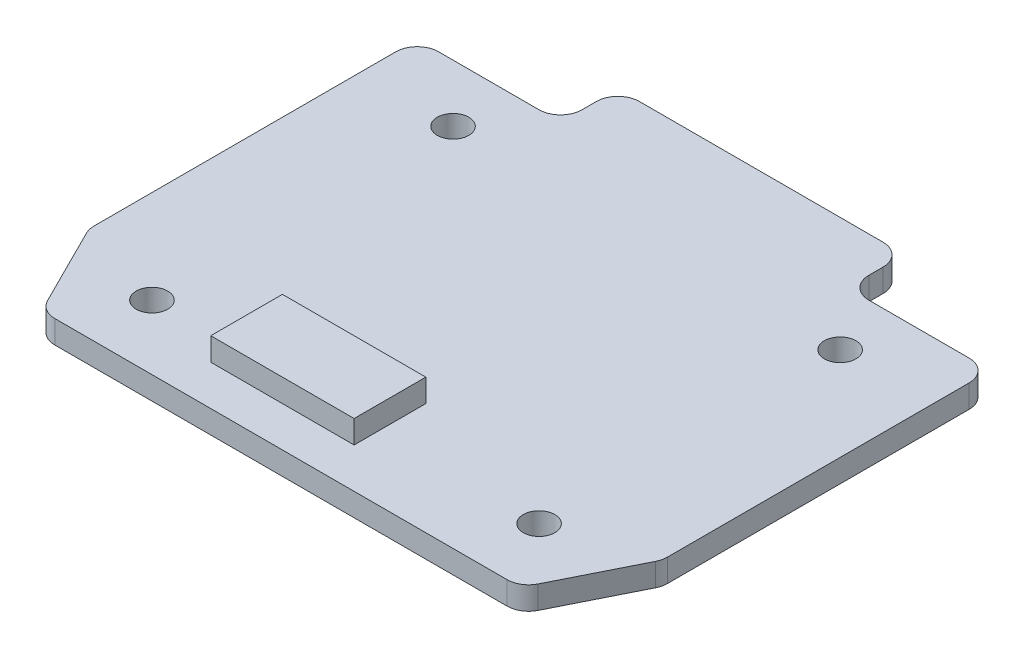
SolidWorks part; units mm, degrees
material "FR4_stuffedProtoboard"
ref_plane "Front Plane" through (0, 0, 0) normal (0, 0, 1) x (1, 0, 0)
ref_plane "Top Plane" through (0, 0, 0) normal (0, 1, 0) x (1, 0, 0)
ref_plane "Right Plane" through (0, 0, 0) normal (1, 0, 0) x (0, 0, -1)
sketch "Sketch1" plane through (0, 0, 0) normal (0, 1, 0) x (1, 0, 0)
  line L0 (-20, 14.75) -> (20, -14.75) construction
  line L1 (-20, 14.75) -> (-10, 14.75)
  line L2 (-20, 14.75) -> (-20, -14.75)
  line L3 (-20, -14.75) -> (20, -14.75)
  line L4 (20, 14.75) -> (20, -14.75)
  line L5 (10, 14.75) -> (20, 14.75)
  line L7 (-10, 14.75) -> (-10, 18.75)
  line L8 (-10, 18.75) -> (10, 18.75)
  line L9 (10, 14.75) -> (10, 18.75)
  line L10 (0, 15.75) -> (10, 18.75) construction
  line L11 (-10, 18.75) -> (0, 15.75) construction
  point P4 (0, 15.75)
  dimension "D1" = 40
  dimension "D2" = 29.5
  dimension "D3" = 20
  dimension "D4" = 4
  dimension "D5" = 20
extrude "Boss-Extrude1" add sketch "Sketch1" along normal blind 1.6
sketch "Sketch4" plane through (0, 0, 0) normal (0, -1, 0) x (1, 0, 0)
  line L0 (-2.2, -5.8223) -> (2.2, -5.8223) construction
  line L1 (-2.2, -0.8223) -> (-2.2, -5.8223) construction
  line L2 (2.2, -0.8223) -> (-2.2, -0.8223) construction
  line L3 (2.2, -5.8223) -> (2.2, -0.8223) construction
  line L12 (-2.2, -5.8223) -> (2.2, -5.8223)
  line L13 (-2.2, -0.8223) -> (-2.2, -5.8223)
  line L14 (2.2, -0.8223) -> (-2.2, -0.8223)
  line L15 (2.2, -5.8223) -> (2.2, -0.8223)
  circle A0 centre (0, -3.3223) radius 0.75 construction
  circle A1 centre (0, -3.3223) radius 0.75
  circle A2 centre (0, -3.3223) radius 3 construction
  circle A3 centre (0, -3.3223) radius 3
sketch "Sketch12" plane through (0, 1.6, 0) normal (0, 1, 0) x (1, 0, 0)
  line L0 (-16.7, -14.75) -> (-20, -8.15)
  line L1 (-20, -14.75) -> (20, -14.75) construction
  line L2 (-20, 14.75) -> (-20, -14.75) construction
  line L3 (-20, -8.15) -> (-20, -14.75)
  line L4 (-20, -14.75) -> (-16.7, -14.75)
  line L5 (16.7, -14.75) -> (20, -8.15)
  line L6 (20, -14.75) -> (20, 14.75) construction
  line L7 (20, -8.15) -> (20, -14.75)
  line L8 (20, -14.75) -> (16.7, -14.75)
  dimension "D1" = 6.6
  dimension "D2" = 3.3
extrude "Cut-Extrude4" cut sketch "Sketch12" against normal through all
hole_wizard "M2 Clearance Hole1" positions "Sketch2" profile "Sketch3" hole size "M2" standard "ANSI Metric"
sketch "Sketch2" plane through (0, 1.6, 0) normal (0, 1, 0) x (1, 0, 0)
  line L1 (-13.5, 10.75) -> (13.5, 10.75)
  line L2 (-13.5, 10.75) -> (-13.5, -10.25)
  line L3 (-13.5, -10.25) -> (13.5, -10.25)
  line L4 (13.5, 10.75) -> (13.5, -10.25)
  line L5 (-16.7, -14.75) -> (16.7, -14.75) construction
  point P0 (-13.5, 10.75)
  point P2 (13.5, 10.75)
  point P4 (13.5, -10.25)
  point P6 (-13.5, -10.25)
  point P142 (0, -10.25)
  dimension "D1" = 21
  dimension "D2" = 27
  dimension "D3" = 4.5
sketch "Sketch3" plane through (-13.5, 1.6, -10.75) normal (1, 0, 0) x (0, 0, 1)
  line L0 (0, 0) -> (0, 5.8609)
  line L1 (0, 5.8609) -> (1.1, 5.2)
  line L2 (1.1, 5.2) -> (1.1, 0)
  line L5 (1.1, 0) -> (0, 0)
  line L10 (0, 5.8609) -> (-1.1, 5.2) construction
  line L11 (0, -6.35) -> (0, 107.95) construction
  dimension "Hole Dia." = 2.2
  dimension "Hole Depth" = 5.2
  dimension "Drill Angle" = 118
hole_wizard "M2 Clearance Hole3" [suppressed] positions "Sketch8" profile "Sketch9" hole size "M2" standard "ANSI Metric"
sketch "Sketch8" plane through (0, 1.6, 0) normal (0, 1, 0) x (1, 0, 0)
  line L0 (-13.5, 12.75) -> (13.5, 12.75)
  line L1 (-13.5, 12.75) -> (-13.5, -10.25)
  line L2 (-13.5, -10.25) -> (13.5, -10.25)
  line L3 (13.5, 12.75) -> (13.5, -10.25)
  line L4 (-17, -14.75) -> (17, -14.75) construction
  point P3 (-13.5, 12.75)
  point P5 (13.5, 12.75)
  point P6 (13.5, -10.25)
  point P7 (-13.5, -10.25)
  point P14 (0, -10.25)
  dimension "D1" = 23
  dimension "D2" = 27
  dimension "D3" = 4.5
sketch "Sketch9" plane through (-13.5, 1.6, -12.75) normal (1, 0, 0) x (0, 0, 1)
  line L0 (0, 0) -> (0, 5.8309)
  line L1 (0, 5.8309) -> (1.05, 5.2)
  line L2 (1.05, 5.2) -> (1.05, 0)
  line L5 (1.05, 0) -> (0, 0)
  line L10 (0, 5.8309) -> (-1.05, 5.2) construction
  line L11 (0, -6.35) -> (0, 107.95) construction
  dimension "Hole Dia." = 2.1
  dimension "Hole Depth" = 5.2
  dimension "Drill Angle" = 118
sketch "Sketch10" [suppressed] plane through (0, 1.6, 0) normal (0, 1, 0) x (1, 0, 0)
  line L0 (-13.5, 12.75) -> (-13.5, 17.75) construction
  line L1 (-14.55, 12.75) -> (-14.55, 17.75)
  line L2 (-12.45, 12.75) -> (-12.45, 17.75)
  line L3 (17, 14.75) -> (-17, 14.75) construction
  line L4 (0, 14.75) -> (0, -14.75) construction
  line L5 (-17, -14.75) -> (17, -14.75) construction
  line L6 (13.5, 12.75) -> (13.5, 17.75) construction
  line L7 (14.55, 12.75) -> (14.55, 17.75)
  line L8 (12.45, 12.75) -> (12.45, 17.75)
  arc A0 (-14.55, 12.75) -> (-12.45, 12.75) centre (-13.5, 12.75) ccw
  arc A1 (-12.45, 17.75) -> (-14.55, 17.75) centre (-13.5, 17.75) ccw
  circle A2 centre (-13.5, 12.75) radius 1.05 construction
  arc A3 (14.55, 12.75) -> (12.45, 12.75) centre (13.5, 12.75) cw
  arc A4 (12.45, 17.75) -> (14.55, 17.75) centre (13.5, 17.75) cw
  point P3 (-13.5, 15.25)
  point P18 (13.5, 15.25)
  dimension "D1" = 3
extrude "Cut-Extrude2" [suppressed] cut sketch "Sketch10" against normal through all both and the other way through all
fillet "Fillet3" [suppressed] radius 1
sketch "Sketch11" plane through (0, 0, 0) normal (0, -1, 0) x (1, 0, 0)
  line L0 (-15, 14.1949) -> (15, 14.1949) construction
  line L4 (-15, 14.1949) -> (15, 14.1949)
  line L5 (15, 14.1949) -> (15, -14.75)
  line L6 (-15, -14.75) -> (15, -14.75)
  line L7 (-15, 14.1949) -> (-15, -14.75)
  line L8 (-10, 11.6949) -> (10, 11.6949) construction
  line L10 (10, -11.7488) -> (-10, -11.7488) construction
  line L12 (-10, 11.6949) -> (10, 11.6949)
  line L13 (-12, -9.748) -> (-12, 9.7506)
  line L14 (10, -11.7488) -> (-10, -11.7488)
  line L15 (12, 9.6375) -> (12, -9.748)
  line L16 (15, 9.25) -> (15, -11.75) construction
  line L17 (-15, 9.25) -> (-15, -11.75) construction
  line L18 (-10, -14.75) -> (-20, -14.75) construction
  circle A0 centre (13.5, -12.75) radius 1 construction
  circle A1 centre (13.5, -12.75) radius 1
  circle A2 centre (13.5, 10.25) radius 1 construction
  circle A3 centre (13.5, 10.25) radius 1
  circle A4 centre (-13.5, -12.75) radius 1 construction
  circle A5 centre (-13.5, -12.75) radius 1
  circle A6 centre (-13.5, 10.25) radius 1 construction
  circle A7 centre (-13.5, 10.25) radius 1
  arc A8 (10, 11.6949) -> (12, 9.6375) centre (10, 9.6941) cw
  arc A9 (-10, 11.6949) -> (-12, 9.7506) centre (-10, 9.6941) ccw
  ellipse E1 centre (-10, -9.748) end of major axis (-10, -7.7472) minor radius 2 (-12, -9.748) -> (-10, -11.7488) ccw construction
  ellipse E2 centre (10, -9.748) end of major axis (10, -7.7472) minor radius 2 (10, -11.7488) -> (12, -9.748) ccw construction
  ellipse E4 centre (10, 9.6941) end of major axis (10, 11.6949) minor radius 2 (11.2574, 11.25) -> (10, 11.6949) ccw construction
  ellipse E5 centre (-10, -9.748) end of major axis (-10, -7.7472) minor radius 2 (-12, -9.748) -> (-10, -11.7488) ccw
  ellipse E6 centre (10, -9.748) end of major axis (10, -7.7472) minor radius 2 (10, -11.7488) -> (12, -9.748) ccw
  ellipse E7 centre (-10, 9.6941) end of major axis (-10, 11.6949) minor radius 2 (-10, 11.6949) -> (-11.2574, 11.25) ccw construction
extrude "Cut-Extrude3" cut sketch "Sketch11" against normal blind 0.001
sketch "boardLayoutOrigin" [suppressed] plane through (0, 0, 0) normal (0, -1, 0) x (1, 0, 0)
  line L0 (20, 11.75) -> (20, -11.75) construction
  line L1 (-17, 14.75) -> (17, 14.75) construction
  point P0 (20, 14.75)
sketch "Sketch13" plane through (0, 1.6, 0) normal (0, 1, 0) x (1, 0, 0)
  line L0 (-20, 14.75) -> (-20, -8.15) construction
  line L1 (-7.7, -11.95) -> (2.3, -11.95)
  line L2 (-7.7, -11.95) -> (-7.7, -6.95)
  line L3 (-7.7, -6.95) -> (2.3, -6.95)
  line L4 (2.3, -11.95) -> (2.3, -6.95)
  line L5 (-7.7, -11.95) -> (2.3, -6.95) construction
  line L6 (-7.7, -6.95) -> (2.3, -11.95) construction
  line L7 (-16.7, -14.75) -> (16.7, -14.75) construction
  point P0 (-2.7, -9.45)
  dimension "D1" = 17.3
  dimension "D2" = 5.3
  dimension "D3" = 10
  dimension "D4" = 5
extrude "Boss-Extrude2" add sketch "Sketch13" along normal blind 1.6 separate body
fillet "Fillet1" radius 1.5 10 edges at (-20, 0.8, -14.75) (20, 0.8, 8.15) (16.7, 0.8, 14.75) (-16.7, 0.8, 14.75) (-20, 0.8, 8.15) (20, 0.8, -14.75) (10, 0.8, -18.75) (10, 0.8005, -14.75) (-10, 0.8, -18.75) (-10, 0.8005, -14.75)
sketch "Sketch14" plane through (0, 0, 0) normal (0, -1, 0) x (1, 0, 0)
  line L0 (-12, -7.25) -> (-12, 6.75) construction
  line L1 (-7, 11.75) -> (7, 11.75) construction
  line L2 (12, 6.75) -> (12, -7.25) construction
  line L3 (7, -12.25) -> (-7, -12.25) construction
  line L4 (-12, -7.25) -> (-12, 6.75)
  line L5 (-7, 11.75) -> (7, 11.75)
  line L6 (12, 6.75) -> (12, -7.25)
  line L7 (7, -12.25) -> (-7, -12.25)
  line L8 (-14, 14.25) -> (19.1305, 14.25) construction
  line L9 (-14, 14.25) -> (19.1305, 14.25)
  line L10 (-15, -13.75) -> (-15, 13.25) construction
  line L11 (-15, -13.75) -> (-15, 13.25)
  line L12 (19.1305, -14.75) -> (-14, -14.75) construction
  line L13 (19.1305, -14.75) -> (-14, -14.75)
  line L14 (26.7763, -0.6973) -> (20.0248, -14.1973) construction
  line L15 (26.7763, -0.6973) -> (20.0248, -14.1973)
  line L16 (20.0248, 13.6973) -> (26.7763, 0.1973) construction
  line L17 (20.0248, 13.6973) -> (26.7763, 0.1973)
  arc A0 (-12, -7.25) -> (-7, -12.25) centre (-7, -7.25) ccw construction
  arc A1 (-7, 11.75) -> (-12, 6.75) centre (-7, 6.75) ccw construction
  arc A2 (12, 6.75) -> (7, 11.75) centre (7, 6.75) ccw construction
  arc A3 (7, -12.25) -> (12, -7.25) centre (7, -7.25) ccw construction
  arc A4 (-12, -7.25) -> (-7, -12.25) centre (-7, -7.25) ccw
  arc A5 (-7, 11.75) -> (-12, 6.75) centre (-7, 6.75) ccw
  arc A6 (12, 6.75) -> (7, 11.75) centre (7, 6.75) ccw
  arc A7 (7, -12.25) -> (12, -7.25) centre (7, -7.25) ccw
  arc A8 (-14, 14.25) -> (-15, 13.25) centre (-14, 13.25) ccw construction
  arc A9 (-14, 14.25) -> (-15, 13.25) centre (-14, 13.25) ccw
  arc A10 (-15, -13.75) -> (-14, -14.75) centre (-14, -13.75) ccw construction
  arc A11 (-15, -13.75) -> (-14, -14.75) centre (-14, -13.75) ccw
  arc A12 (19.1305, -14.75) -> (20.0248, -14.1973) centre (19.1305, -13.75) ccw construction
  arc A13 (19.1305, -14.75) -> (20.0248, -14.1973) centre (19.1305, -13.75) ccw
  arc A14 (20.0248, 13.6973) -> (19.1305, 14.25) centre (19.1305, 13.25) ccw construction
  arc A15 (26.7763, -0.6973) -> (26.7763, 0.1973) centre (25.8819, -0.25) ccw construction
  arc A16 (20.0248, 13.6973) -> (19.1305, 14.25) centre (19.1305, 13.25) ccw
  arc A17 (26.7763, -0.6973) -> (26.7763, 0.1973) centre (25.8819, -0.25) ccw
sketch "Sketch15" plane through (0, 0, 0) normal (0, -1, 0) x (1, 0, 0)
  line L0 (-7, 11.75) -> (7, 11.75) construction
  line L1 (-12, -7.25) -> (-12, 6.75) construction
  line L2 (7, -12.25) -> (-7, -12.25) construction
  line L3 (-7, 11.75) -> (7, 11.75)
  line L4 (-12, -7.25) -> (-12, 6.75)
  line L5 (7, -12.25) -> (-7, -12.25)
  line L6 (12, 6.75) -> (12, -7.25) construction
  line L7 (12, 6.75) -> (12, -7.25)
  line L8 (14, -14.75) -> (-19.1305, -14.75) construction
  line L9 (-20.0248, -14.1973) -> (-26.7763, -0.6973) construction
  line L10 (-26.7763, 0.1973) -> (-20.0248, 13.6973) construction
  line L11 (15, 13.25) -> (15, -13.75) construction
  line L12 (-19.1305, 14.25) -> (14, 14.25) construction
  line L13 (14, -14.75) -> (-19.1305, -14.75)
  line L14 (-20.0248, -14.1973) -> (-26.7763, -0.6973)
  line L15 (-26.7763, 0.1973) -> (-20.0248, 13.6973)
  line L16 (15, 13.25) -> (15, -13.75)
  line L17 (-19.1305, 14.25) -> (14, 14.25)
  arc A0 (-7, 11.75) -> (-12, 6.75) centre (-7, 6.75) ccw construction
  arc A1 (-12, -7.25) -> (-7, -12.25) centre (-7, -7.25) ccw construction
  arc A2 (7, -12.25) -> (12, -7.25) centre (7, -7.25) ccw construction
  arc A3 (-7, 11.75) -> (-12, 6.75) centre (-7, 6.75) ccw
  arc A4 (-12, -7.25) -> (-7, -12.25) centre (-7, -7.25) ccw
  arc A5 (7, -12.25) -> (12, -7.25) centre (7, -7.25) ccw
  arc A6 (12, 6.75) -> (7, 11.75) centre (7, 6.75) ccw construction
  arc A7 (12, 6.75) -> (7, 11.75) centre (7, 6.75) ccw
  arc A8 (14, -14.75) -> (15, -13.75) centre (14, -13.75) ccw construction
  arc A9 (-20.0248, -14.1973) -> (-19.1305, -14.75) centre (-19.1305, -13.75) ccw construction
  arc A10 (-26.7763, 0.1973) -> (-26.7763, -0.6973) centre (-25.8819, -0.25) ccw construction
  arc A11 (-19.1305, 14.25) -> (-20.0248, 13.6973) centre (-19.1305, 13.25) ccw construction
  arc A12 (15, 13.25) -> (14, 14.25) centre (14, 13.25) ccw construction
  arc A13 (14, -14.75) -> (15, -13.75) centre (14, -13.75) ccw
  arc A14 (-20.0248, -14.1973) -> (-19.1305, -14.75) centre (-19.1305, -13.75) ccw
  arc A15 (-26.7763, 0.1973) -> (-26.7763, -0.6973) centre (-25.8819, -0.25) ccw
  arc A16 (-19.1305, 14.25) -> (-20.0248, 13.6973) centre (-19.1305, 13.25) ccw
  arc A17 (15, 13.25) -> (14, 14.25) centre (14, 13.25) ccw
sketch "Sketch16" plane through (0, 1.6, 0) normal (0, 1, 0) x (1, 0, 0)
  circle A0 centre (13.5, -10.25) radius 2.25 construction
  circle A1 centre (13.5, 10.75) radius 2.25 construction
  circle A2 centre (-13.5, 10.75) radius 2.25 construction
  circle A3 centre (-13.5, -10.25) radius 2.25 construction
  circle A4 centre (13.5, -10.25) radius 2.25
  circle A5 centre (13.5, 10.75) radius 2.25
  circle A6 centre (-13.5, 10.75) radius 2.25
  circle A7 centre (-13.5, -10.25) radius 2.25
